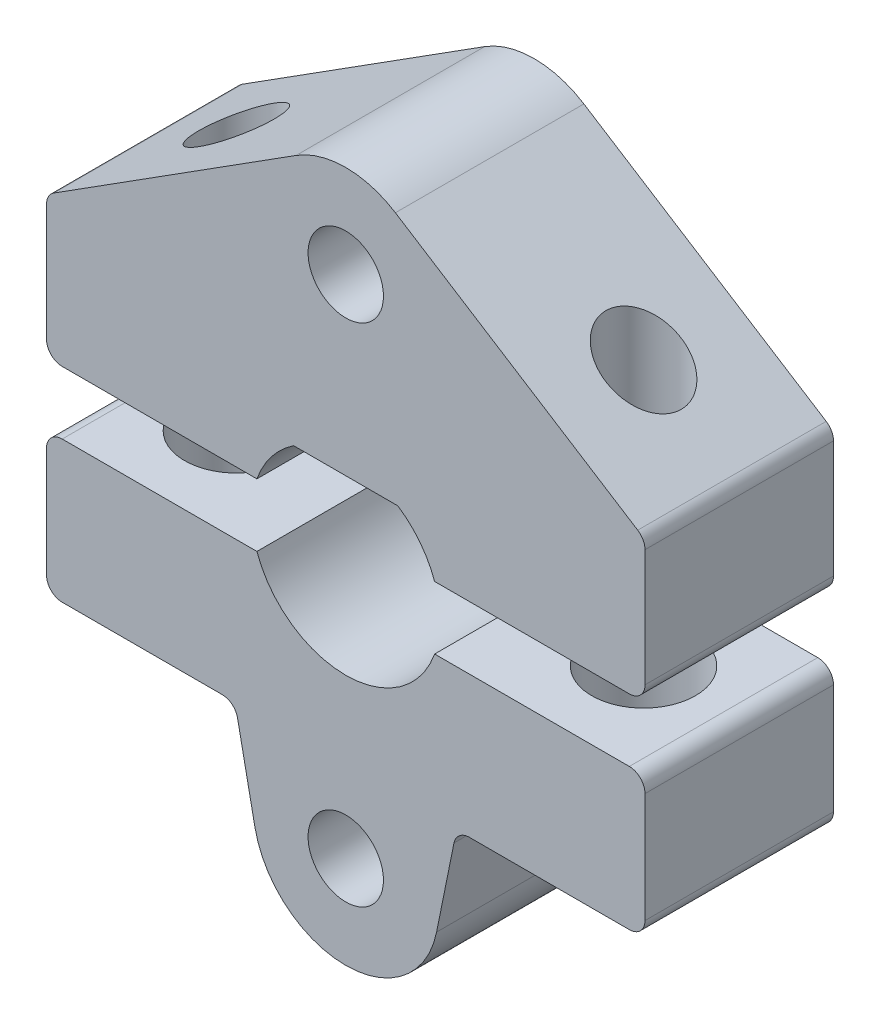
SolidWorks part; units mm, degrees
material "6061-T6 (SS)"
ref_plane "前视基准面" through (0, 0, 0) normal (0, 0, 1) x (1, 0, 0)
ref_plane "上视基准面" through (0, 0, 0) normal (0, 1, 0) x (1, 0, 0)
ref_plane "右视基准面" through (0, 0, 0) normal (1, 0, 0) x (0, 0, -1)
sketch "草图1" plane through (0, 0, 0) normal (0, 0, 1) x (1, 0, 0)
  line L0 (-1.6583, 2.5) -> (1.6583, 2.5)
  line L1 (-9.2941, 5.6473) -> (-1.5803, 10.541)
  line L2 (1.5803, 10.541) -> (9.2941, 5.6473)
  line L3 (-9.5263, 5.2251) -> (-9.5263, 1.5)
  line L4 (-9.0263, 1) -> (-2.8284, 1)
  line L5 (9.5263, 1.5) -> (9.5263, 5.2251)
  line L6 (0, 1) -> (0, 0) construction
  line L7 (-9.0263, -1) -> (-2.8284, -1)
  line L8 (9.5263, -1.5) -> (9.5263, -5)
  line L9 (9.0263, -5.5) -> (3.9352, -5.5)
  line L10 (3.4451, -5.9008) -> (2.8913, -8.6355)
  line L11 (-2.8913, -8.6355) -> (-3.4451, -5.9008)
  line L12 (-3.9352, -5.5) -> (-9.0263, -5.5)
  line L13 (-9.5263, -5) -> (-9.5263, -1.5)
  line L14 (0, 0) -> (0, -1) construction
  line L15 (2.8284, 1) -> (9.0263, 1)
  line L16 (2.8284, -1) -> (9.0263, -1)
  line L17 (9.2941, 5.6473) -> (9.5263, 5.5) construction
  line L18 (9.5263, 5.5) -> (9.5263, 5.2251) construction
  arc A0 (-1.6583, 2.5) -> (-2.8284, 1) centre (0, 0) ccw
  circle A1 centre (0, 0) radius 8.05 construction
  circle A2 centre (0, 8.05) radius 1.2
  circle A3 centre (0, -8.05) radius 1.2
  arc A4 (-1.5803, 10.541) -> (1.5803, 10.541) centre (0, 8.05) cw
  circle A5 centre (0, 0) radius 11 construction
  arc A6 (2.8913, -8.6355) -> (-2.8913, -8.6355) centre (0, -8.05) cw
  arc A7 (-9.5263, 1.5) -> (-9.0263, 1) centre (-9.0263, 1.5) ccw
  arc A8 (-9.2941, 5.6473) -> (-9.5263, 5.2251) centre (-9.0263, 5.2251) ccw
  arc A9 (9.2941, 5.6473) -> (9.5263, 5.2251) centre (9.0263, 5.2251) cw
  arc A10 (9.0263, 1) -> (9.5263, 1.5) centre (9.0263, 1.5) ccw
  arc A11 (-9.0263, -5.5) -> (-9.5263, -5) centre (-9.0263, -5) cw
  arc A12 (-9.0263, -1) -> (-9.5263, -1.5) centre (-9.0263, -1.5) ccw
  arc A13 (9.5263, -5) -> (9.0263, -5.5) centre (9.0263, -5) cw
  arc A14 (9.0263, -1) -> (9.5263, -1.5) centre (9.0263, -1.5) cw
  arc A15 (3.9352, -5.5) -> (3.4451, -5.9008) centre (3.9352, -6) ccw
  arc A16 (-3.4451, -5.9008) -> (-3.9352, -5.5) centre (-3.9352, -6) ccw
  arc A17 (-2.8284, -1) -> (2.8284, -1) centre (0, 0) ccw
  arc A18 (2.8284, 1) -> (1.6583, 2.5) centre (0, 0) ccw
  point P31 (-9.5263, 1)
  point P34 (-9.5263, 5.5)
  point P39 (9.5263, 1)
  point P42 (-9.5263, -5.5)
  point P47 (9.5263, -5.5)
  point P52 (3.5263, -5.5)
  dimension "D1" = 16.1
  dimension "D2" = 6
  dimension "D4" = 2.4
  dimension "D6" = 22
  dimension "D10" = 0.5
  dimension "D5" = 4.5
  dimension "D3" = 2.5
  dimension "D7" = 1
  dimension "D9" = 6
extrude "凸台-拉伸1" add sketch "草图1" along normal mid plane 6
cosmetic thread "装饰螺纹线3"
cosmetic thread "装饰螺纹线4"
sketch "草图2" plane through (0, -5.5, 0) normal (0, -1, 0) x (1, 0, 0)
  line L0 (-9.5263, 0) -> (-6.4807, 0) construction
  line L1 (-9.5263, 3) -> (-9.5263, -3) construction
  line L2 (-6.4807, 0) -> (6.4807, 0) construction
  line L3 (6.4807, 0) -> (9.5263, 0) construction
  line L4 (9.5263, 3) -> (9.5263, -3) construction
  line L5 (6.4807, 3) -> (6.4807, 0) construction
  line L6 (3.9352, 3) -> (9.0263, 3) construction
  circle A0 centre (6.4807, 0) radius 1.2
  circle A1 centre (-6.4807, 0) radius 1.2
  dimension "D1" = 2.4
extrude "切除-拉伸1" cut sketch "草图2" against normal through all
cosmetic thread "装饰螺纹线1" parameters "D2"=3
cosmetic thread "装饰螺纹线2" parameters "D2"=3
sketch "草图3" plane through (0, -5.5, 0) normal (0, -1, 0) x (1, 0, 0)
  circle A0 centre (-6.4807, 0) radius 1.65
  circle A1 centre (6.4807, 0) radius 1.65
  dimension "D1" = 3.3
extrude "切除-拉伸2" cut sketch "草图3" against normal up to surface (4.5 mm away) up to face at (-5.2807, -1, 0)
